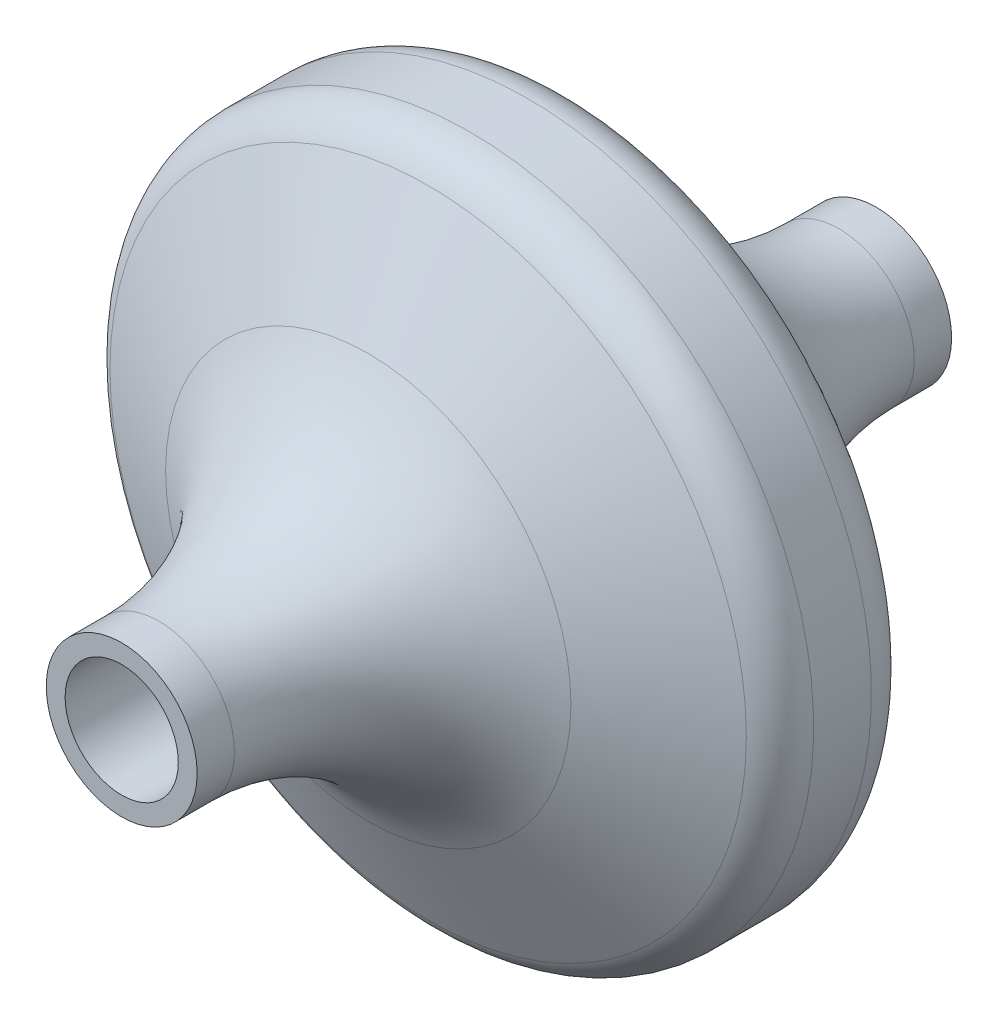
SolidWorks part; units mm, degrees
ref_plane "Front Plane" through (0, 0, 0) normal (0, 0, 1) x (1, 0, 0)
ref_plane "Top Plane" through (0, 0, 0) normal (0, 1, 0) x (1, 0, 0)
ref_plane "Right Plane" through (0, 0, 0) normal (1, 0, 0) x (0, 0, -1)
sketch "Sketch1" plane through (0, 0, 0) normal (0, 0, 1) x (1, 0, 0)
  circle A0 centre (0, 0) radius 6
  circle A1 centre (0, 0) radius 8
  dimension "D1" = 16
  dimension "D2" = 12
extrude "Boss-Extrude1" add sketch "Sketch1" along normal mid plane 80
sketch "Sketch2" plane through (0, 0, 0) normal (1, 0, 0) x (0, 0, -1)
  line L0 (-25, 0) -> (-7.503, 33.7373)
  line L1 (-3.0644, 36.4353) -> (3.0644, 36.4353)
  line L2 (7.503, 33.7373) -> (25, 0)
  line L3 (25, 0) -> (-25, 0) construction
  line L4 (-25, 0) -> (25, 0)
  arc A1 (-7.503, 33.7373) -> (-3.0644, 36.4353) centre (-3.0644, 31.4353) cw
  arc A2 (7.503, 33.7373) -> (3.0644, 36.4353) centre (3.0644, 31.4353) ccw
  point P2 (0, 36.4353)
  point P3 (-3.0644, 36.4353)
  point P20 (6.1037, 36.4353)
  dimension "D1" = 50
  dimension "D2" = 5
revolve "Revolve1" add sketch "Sketch2" angle 360 about L3
fillet "Fillet1" radius 25 2 edges at (8, 0, -20.851) (-8, 0, 20.851)
